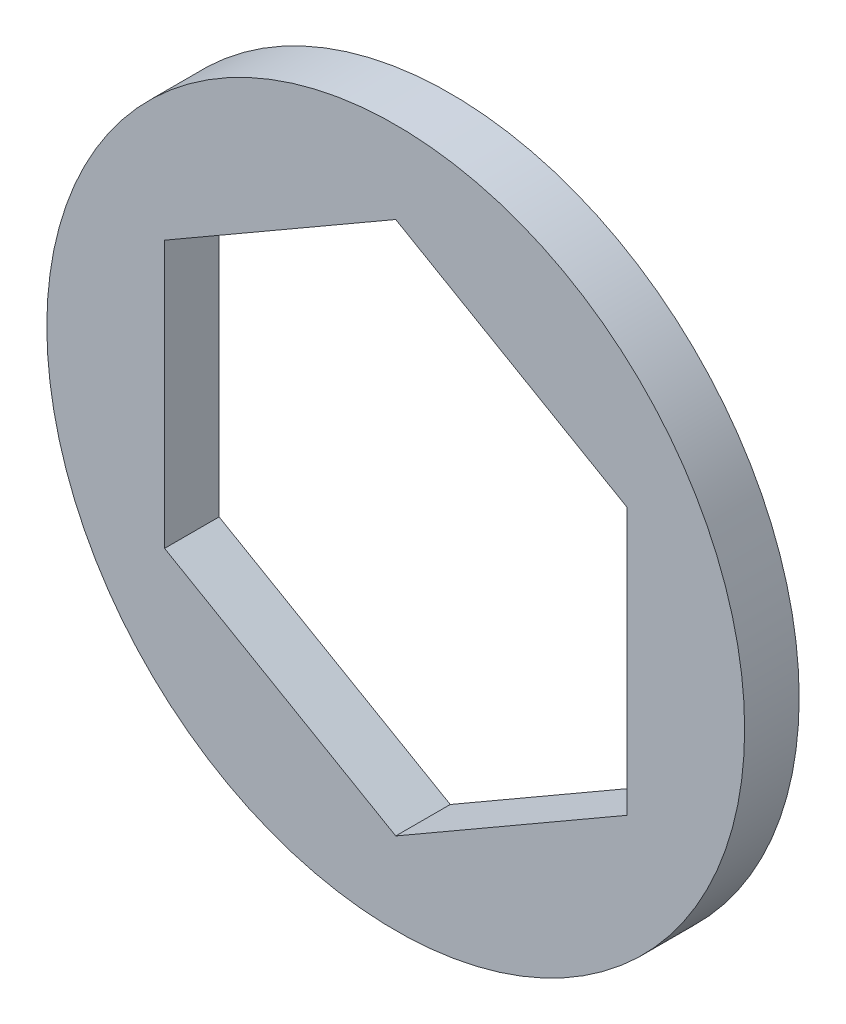
SolidWorks part; units mm, degrees
material "Nylon 101"
ref_plane "Front Plane" through (0, 0, 0) normal (0, 0, 1) x (1, 0, 0)
ref_plane "Top Plane" through (0, 0, 0) normal (0, 1, 0) x (1, 0, 0)
ref_plane "Right Plane" through (0, 0, 0) normal (1, 0, 0) x (0, 0, -1)
sketch "Sketch1" plane through (0, 0, 0) normal (0, 0, 1) x (1, 0, 0)
  line L1 (0, 7.7723) -> (-6.731, 3.8861)
  line L2 (-6.731, 3.8861) -> (-6.731, -3.8861)
  line L3 (-6.731, -3.8861) -> (0, -7.7723)
  line L4 (0, -7.7723) -> (6.731, -3.8861)
  line L5 (6.731, -3.8861) -> (6.731, 3.8861)
  line L6 (6.731, 3.8861) -> (0, 7.7723)
  circle A0 centre (0, 0) radius 10.16
  circle A1 centre (0, 0) radius 6.731 construction
  dimension "D1" = 20.32
  dimension "D2" = 13.462
extrude "Boss-Extrude1" add sketch "Sketch1" along normal mid plane 1.5875
